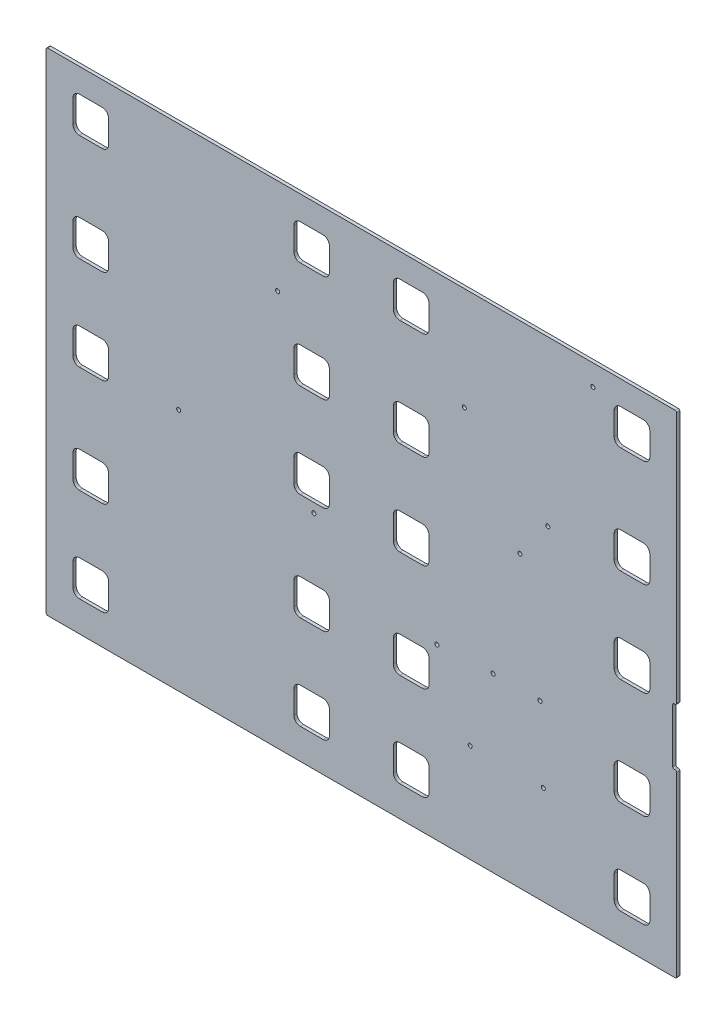
SolidWorks part; units mm, degrees
material "PP Film"
ref_plane "X-Y Datum" through (0, 0, 0) normal (0, 0, 1) x (1, 0, 0)
ref_plane "X-Z Datum" through (0, 0, 0) normal (0, 1, 0) x (1, 0, 0)
ref_plane "Y-Z Datum" through (0, 0, 0) normal (1, 0, 0) x (0, 0, -1)
sketch "Sketch9" plane through (0, 0, 0) normal (0, 0, 1) x (1, 0, 0)
  line L0 (-82.7559, -182.5893) -> (-82.7583, -160.1613) construction
  line L1 (-89.109, -153.8119) -> (-111.537, -153.8143) construction
  line L2 (-117.8863, -160.165) -> (-117.8839, -182.593) construction
  line L3 (-111.5333, -188.9423) -> (-89.1053, -188.9399) construction
  line L4 (476.8831, 172.8027) -> (-144.3755, 172.7375)
  line L12 (-111.5443, -83.8117) -> (-89.1163, -83.8093) construction
  line L13 (-82.767, -77.4587) -> (-82.7693, -55.0307) construction
  line L14 (-89.12, -48.6813) -> (-111.548, -48.6837) construction
  line L15 (-117.8973, -55.0344) -> (-117.895, -77.4624) construction
  line L16 (-82.7877, 120.2549) -> (-82.7901, 142.6829) construction
  line L17 (-89.1408, 149.0323) -> (-111.5688, 149.0299) construction
  line L18 (-117.9181, 142.6792) -> (-117.9157, 120.2512) construction
  line L19 (-111.5651, 113.9019) -> (-89.1371, 113.9043) construction
  line L20 (-111.554, 8.7713) -> (-89.126, 8.7737) construction
  line L21 (-117.9071, 37.5486) -> (-117.9047, 15.1206) construction
  line L22 (-89.1297, 43.9017) -> (-111.5577, 43.8993) construction
  line L23 (-82.7767, 15.1243) -> (-82.7791, 37.5523) construction
  line L24 (-82.7559, -182.5893) -> (-82.7583, -160.1613)
  line L25 (-89.109, -153.8119) -> (-111.537, -153.8143)
  line L26 (-117.8863, -160.165) -> (-117.8839, -182.593)
  line L27 (-111.5333, -188.9423) -> (-89.1053, -188.9399)
  line L28 (-111.5443, -83.8117) -> (-89.1163, -83.8093)
  line L29 (-82.767, -77.4587) -> (-82.7693, -55.0307)
  line L30 (-89.12, -48.6813) -> (-111.548, -48.6837)
  line L31 (-117.8973, -55.0344) -> (-117.895, -77.4624)
  line L32 (-82.7877, 120.2549) -> (-82.7901, 142.6829)
  line L33 (-89.1408, 149.0323) -> (-111.5688, 149.0299)
  line L34 (-117.9181, 142.6792) -> (-117.9157, 120.2512)
  line L35 (-111.5651, 113.9019) -> (-89.1371, 113.9043)
  line L36 (-111.554, 8.7713) -> (-89.126, 8.7737)
  line L37 (-117.9071, 37.5486) -> (-117.9047, 15.1206)
  line L38 (-89.1297, 43.9017) -> (-111.5577, 43.8993)
  line L39 (-82.7767, 15.1243) -> (-82.7791, 37.5523)
  line L40 (-82.7462, -275.1723) -> (-82.7486, -252.7443) construction
  line L41 (-89.0992, -246.3949) -> (-111.5272, -246.3973) construction
  line L42 (-117.8766, -252.748) -> (-117.8742, -275.176) construction
  line L43 (-111.5235, -281.5253) -> (-89.0955, -281.5229) construction
  line L44 (-82.7462, -275.1723) -> (-82.7486, -252.7443)
  line L45 (-89.0992, -246.3949) -> (-111.5272, -246.3973)
  line L46 (-117.8766, -252.748) -> (-117.8742, -275.176)
  line L47 (-111.5235, -281.5253) -> (-89.0955, -281.5229)
  line L82 (476.8831, 172.8027) -> (-144.3755, 172.7375)
  line L83 (-144.3755, 172.7375) -> (-144.3246, -311.5135)
  line L84 (-144.3755, 172.7375) -> (-144.3246, -311.5135)
  line L85 (-144.3246, -311.5135) -> (476.934, -311.4483)
  line L86 (-144.3246, -311.5135) -> (476.934, -311.4483)
  line L87 (476.934, -311.4483) -> (476.8831, 172.8027)
  line L88 (476.934, -311.4483) -> (476.8831, 172.8027)
  arc A0 (-89.1053, -188.9399) -> (-82.7559, -182.5893) centre (-89.1059, -182.5899) ccw construction
  arc A1 (-82.7583, -160.1613) -> (-89.109, -153.8119) centre (-89.1083, -160.1619) ccw construction
  arc A2 (-111.537, -153.8143) -> (-117.8863, -160.165) centre (-111.5363, -160.1643) ccw construction
  arc A3 (-117.8839, -182.593) -> (-111.5333, -188.9423) centre (-111.5339, -182.5923) ccw construction
  arc A4 (-89.1163, -83.8093) -> (-82.767, -77.4587) centre (-89.117, -77.4593) ccw construction
  arc A5 (-82.7693, -55.0307) -> (-89.12, -48.6813) centre (-89.1193, -55.0313) ccw construction
  arc A6 (-111.548, -48.6837) -> (-117.8973, -55.0344) centre (-111.5473, -55.0337) ccw construction
  arc A7 (-117.895, -77.4624) -> (-111.5443, -83.8117) centre (-111.545, -77.4617) ccw construction
  arc A8 (-89.1371, 113.9043) -> (-82.7877, 120.2549) centre (-89.1377, 120.2543) ccw construction
  arc A9 (-82.7901, 142.6829) -> (-89.1408, 149.0323) centre (-89.1401, 142.6823) ccw construction
  arc A10 (-111.5688, 149.0299) -> (-117.9181, 142.6792) centre (-111.5681, 142.6799) ccw construction
  arc A11 (-117.9157, 120.2512) -> (-111.5651, 113.9019) centre (-111.5657, 120.2519) ccw construction
  arc A12 (-82.7791, 37.5523) -> (-89.1297, 43.9017) centre (-89.1291, 37.5517) ccw construction
  arc A13 (-89.126, 8.7737) -> (-82.7767, 15.1243) centre (-89.1267, 15.1237) ccw construction
  arc A14 (-117.9047, 15.1206) -> (-111.554, 8.7713) centre (-111.5547, 15.1213) ccw construction
  arc A15 (-111.5577, 43.8993) -> (-117.9071, 37.5486) centre (-111.5571, 37.5493) ccw construction
  arc A16 (-89.1053, -188.9399) -> (-82.7559, -182.5893) centre (-89.1059, -182.5899) ccw
  arc A17 (-82.7583, -160.1613) -> (-89.109, -153.8119) centre (-89.1083, -160.1619) ccw
  arc A18 (-111.537, -153.8143) -> (-117.8863, -160.165) centre (-111.5363, -160.1643) ccw
  arc A19 (-117.8839, -182.593) -> (-111.5333, -188.9423) centre (-111.5339, -182.5923) ccw
  arc A20 (-89.1163, -83.8093) -> (-82.767, -77.4587) centre (-89.117, -77.4593) ccw
  arc A21 (-82.7693, -55.0307) -> (-89.12, -48.6813) centre (-89.1193, -55.0313) ccw
  arc A22 (-111.548, -48.6837) -> (-117.8973, -55.0344) centre (-111.5473, -55.0337) ccw
  arc A23 (-117.895, -77.4624) -> (-111.5443, -83.8117) centre (-111.545, -77.4617) ccw
  arc A24 (-89.1371, 113.9043) -> (-82.7877, 120.2549) centre (-89.1377, 120.2543) ccw
  arc A25 (-82.7901, 142.6829) -> (-89.1408, 149.0323) centre (-89.1401, 142.6823) ccw
  arc A26 (-111.5688, 149.0299) -> (-117.9181, 142.6792) centre (-111.5681, 142.6799) ccw
  arc A27 (-117.9157, 120.2512) -> (-111.5651, 113.9019) centre (-111.5657, 120.2519) ccw
  arc A28 (-82.7791, 37.5523) -> (-89.1297, 43.9017) centre (-89.1291, 37.5517) ccw
  arc A29 (-89.126, 8.7737) -> (-82.7767, 15.1243) centre (-89.1267, 15.1237) ccw
  arc A30 (-117.9047, 15.1206) -> (-111.554, 8.7713) centre (-111.5547, 15.1213) ccw
  arc A31 (-111.5577, 43.8993) -> (-117.9071, 37.5486) centre (-111.5571, 37.5493) ccw
  arc A32 (-89.0955, -281.5229) -> (-82.7462, -275.1723) centre (-89.0962, -275.1729) ccw construction
  arc A33 (-111.5272, -246.3973) -> (-117.8766, -252.748) centre (-111.5266, -252.7473) ccw construction
  arc A34 (-117.8742, -275.176) -> (-111.5235, -281.5253) centre (-111.5242, -275.1753) ccw construction
  arc A35 (-89.0955, -281.5229) -> (-82.7462, -275.1723) centre (-89.0962, -275.1729) ccw
  arc A36 (-111.5272, -246.3973) -> (-117.8766, -252.748) centre (-111.5266, -252.7473) ccw
  arc A37 (-117.8742, -275.176) -> (-111.5235, -281.5253) centre (-111.5242, -275.1753) ccw
  arc A38 (-82.7486, -252.7443) -> (-89.0992, -246.3949) centre (-89.0986, -252.7449) ccw construction
  arc A39 (-82.7486, -252.7443) -> (-89.0992, -246.3949) centre (-89.0986, -252.7449) ccw
  dimension "D1" = 0
extrude "Boss-Extrude2" add sketch "Sketch9" along normal blind 3.175
sketch "Sketch10" plane through (0, 0, 3.175) normal (0, 0, 1) x (1, 0, 0)
  line L9 (476.8831, 172.8027) -> (-144.3755, 172.7375)
  line L10 (-144.3755, 172.7375) -> (-144.3246, -311.5135)
  line L11 (-144.3246, -311.5135) -> (476.934, -311.4483)
  line L12 (-117.8863, -160.165) -> (-117.8839, -182.593)
  line L13 (-111.5333, -188.9423) -> (-89.1053, -188.9399)
  line L14 (-82.7559, -182.5893) -> (-82.7583, -160.1613)
  line L15 (-89.109, -153.8119) -> (-111.537, -153.8143)
  line L16 (-117.8863, -160.165) -> (-117.8839, -182.593)
  line L17 (-111.5333, -188.9423) -> (-89.1053, -188.9399)
  line L18 (-82.7559, -182.5893) -> (-82.7583, -160.1613)
  line L19 (-89.109, -153.8119) -> (-111.537, -153.8143)
  line L20 (-117.8766, -252.748) -> (-117.8742, -275.176)
  line L21 (-89.0992, -246.3949) -> (-111.5272, -246.3973)
  line L22 (-82.7462, -275.1723) -> (-82.7486, -252.7443)
  line L23 (-111.5235, -281.5253) -> (-89.0955, -281.5229)
  line L24 (-117.8766, -252.748) -> (-117.8742, -275.176)
  line L25 (-89.0992, -246.3949) -> (-111.5272, -246.3973)
  line L26 (-82.7462, -275.1723) -> (-82.7486, -252.7443)
  line L27 (-111.5235, -281.5253) -> (-89.0955, -281.5229)
  line L28 (-89.12, -48.6813) -> (-111.548, -48.6837)
  line L29 (-117.8973, -55.0344) -> (-117.895, -77.4624)
  line L30 (-111.5443, -83.8117) -> (-89.1163, -83.8093)
  line L31 (-82.767, -77.4587) -> (-82.7693, -55.0307)
  line L32 (-89.12, -48.6813) -> (-111.548, -48.6837)
  line L33 (-117.8973, -55.0344) -> (-117.895, -77.4624)
  line L34 (-111.5443, -83.8117) -> (-89.1163, -83.8093)
  line L35 (-82.767, -77.4587) -> (-82.7693, -55.0307)
  line L36 (-82.7877, 120.2549) -> (-82.7901, 142.6829)
  line L37 (-111.5651, 113.9019) -> (-89.1371, 113.9043)
  line L38 (-117.9181, 142.6792) -> (-117.9157, 120.2512)
  line L39 (-89.1408, 149.0323) -> (-111.5688, 149.0299)
  line L40 (-82.7877, 120.2549) -> (-82.7901, 142.6829)
  line L41 (-111.5651, 113.9019) -> (-89.1371, 113.9043)
  line L42 (-117.9181, 142.6792) -> (-117.9157, 120.2512)
  line L43 (-89.1408, 149.0323) -> (-111.5688, 149.0299)
  line L44 (-111.554, 8.7713) -> (-89.126, 8.7737)
  line L45 (-82.7767, 15.1243) -> (-82.7791, 37.5523)
  line L46 (-89.1297, 43.9017) -> (-111.5577, 43.8993)
  line L47 (-117.9071, 37.5486) -> (-117.9047, 15.1206)
  line L48 (-111.554, 8.7713) -> (-89.126, 8.7737)
  line L49 (-82.7767, 15.1243) -> (-82.7791, 37.5523)
  line L50 (-89.1297, 43.9017) -> (-111.5577, 43.8993)
  line L51 (-117.9071, 37.5486) -> (-117.9047, 15.1206)
  line L53 (476.934, -311.4483) -> (476.8831, 172.8027)
  arc A4 (-117.8839, -182.593) -> (-111.5333, -188.9423) centre (-111.5339, -182.5923) ccw
  arc A5 (-89.1053, -188.9399) -> (-82.7559, -182.5893) centre (-89.1059, -182.5899) ccw
  arc A6 (-82.7583, -160.1613) -> (-89.109, -153.8119) centre (-89.1083, -160.1619) ccw
  arc A7 (-111.537, -153.8143) -> (-117.8863, -160.165) centre (-111.5363, -160.1643) ccw
  arc A8 (-117.8839, -182.593) -> (-111.5333, -188.9423) centre (-111.5339, -182.5923) ccw
  arc A9 (-89.1053, -188.9399) -> (-82.7559, -182.5893) centre (-89.1059, -182.5899) ccw
  arc A10 (-82.7583, -160.1613) -> (-89.109, -153.8119) centre (-89.1083, -160.1619) ccw
  arc A11 (-111.537, -153.8143) -> (-117.8863, -160.165) centre (-111.5363, -160.1643) ccw
  arc A12 (-111.5272, -246.3973) -> (-117.8766, -252.748) centre (-111.5266, -252.7473) ccw
  arc A13 (-82.7486, -252.7443) -> (-89.0992, -246.3949) centre (-89.0986, -252.7449) ccw
  arc A14 (-89.0955, -281.5229) -> (-82.7462, -275.1723) centre (-89.0962, -275.1729) ccw
  arc A15 (-117.8742, -275.176) -> (-111.5235, -281.5253) centre (-111.5242, -275.1753) ccw
  arc A16 (-111.5272, -246.3973) -> (-117.8766, -252.748) centre (-111.5266, -252.7473) ccw
  arc A17 (-82.7486, -252.7443) -> (-89.0992, -246.3949) centre (-89.0986, -252.7449) ccw
  arc A18 (-89.0955, -281.5229) -> (-82.7462, -275.1723) centre (-89.0962, -275.1729) ccw
  arc A19 (-117.8742, -275.176) -> (-111.5235, -281.5253) centre (-111.5242, -275.1753) ccw
  arc A20 (-111.548, -48.6837) -> (-117.8973, -55.0344) centre (-111.5473, -55.0337) ccw
  arc A21 (-117.895, -77.4624) -> (-111.5443, -83.8117) centre (-111.545, -77.4617) ccw
  arc A22 (-89.1163, -83.8093) -> (-82.767, -77.4587) centre (-89.117, -77.4593) ccw
  arc A23 (-82.7693, -55.0307) -> (-89.12, -48.6813) centre (-89.1193, -55.0313) ccw
  arc A24 (-111.548, -48.6837) -> (-117.8973, -55.0344) centre (-111.5473, -55.0337) ccw
  arc A25 (-117.895, -77.4624) -> (-111.5443, -83.8117) centre (-111.545, -77.4617) ccw
  arc A26 (-89.1163, -83.8093) -> (-82.767, -77.4587) centre (-89.117, -77.4593) ccw
  arc A27 (-82.7693, -55.0307) -> (-89.12, -48.6813) centre (-89.1193, -55.0313) ccw
  arc A28 (-89.1371, 113.9043) -> (-82.7877, 120.2549) centre (-89.1377, 120.2543) ccw
  arc A29 (-117.9157, 120.2512) -> (-111.5651, 113.9019) centre (-111.5657, 120.2519) ccw
  arc A30 (-111.5688, 149.0299) -> (-117.9181, 142.6792) centre (-111.5681, 142.6799) ccw
  arc A31 (-82.7901, 142.6829) -> (-89.1408, 149.0323) centre (-89.1401, 142.6823) ccw
  arc A32 (-89.1371, 113.9043) -> (-82.7877, 120.2549) centre (-89.1377, 120.2543) ccw
  arc A33 (-117.9157, 120.2512) -> (-111.5651, 113.9019) centre (-111.5657, 120.2519) ccw
  arc A34 (-111.5688, 149.0299) -> (-117.9181, 142.6792) centre (-111.5681, 142.6799) ccw
  arc A35 (-82.7901, 142.6829) -> (-89.1408, 149.0323) centre (-89.1401, 142.6823) ccw
  arc A36 (-89.126, 8.7737) -> (-82.7767, 15.1243) centre (-89.1267, 15.1237) ccw
  arc A37 (-82.7791, 37.5523) -> (-89.1297, 43.9017) centre (-89.1291, 37.5517) ccw
  arc A38 (-111.5577, 43.8993) -> (-117.9071, 37.5486) centre (-111.5571, 37.5493) ccw
  arc A39 (-117.9047, 15.1206) -> (-111.554, 8.7713) centre (-111.5547, 15.1213) ccw
  arc A40 (-89.126, 8.7737) -> (-82.7767, 15.1243) centre (-89.1267, 15.1237) ccw
  arc A41 (-82.7791, 37.5523) -> (-89.1297, 43.9017) centre (-89.1291, 37.5517) ccw
  arc A42 (-111.5577, 43.8993) -> (-117.9071, 37.5486) centre (-111.5571, 37.5493) ccw
  arc A43 (-117.9047, 15.1206) -> (-111.554, 8.7713) centre (-111.5547, 15.1213) ccw
  dimension "D2" = 0
  dimension "D3" = 0
  dimension "D4" = 0
  dimension "D5" = 0
  dimension "D6" = 0
extrude "Cut-Extrude6" cut sketch "Sketch10" against normal through all contours L40 A35 L43 A34 L42 A33 L41 A32 | L51 A43 L48 A40 L49 A41 L50 A42 | L35 A27 L32 A24 L33 A25 L34 A26 | L19 A11 L16 A8 L17 A9 L18 A10 | L24 A19 L27 A18 L26 A17 L25 A16
pattern_linear "LPattern2" count 2 spacing 217.5764 along (1, 0.0001, 0) of "Cut-Extrude6"
ref_plane "Plane1" through (166.272, 0.0175, 0) normal (-1, -0.0001, 0) x (0, 0, 1)
mirror "Mirror1" about plane through (166.272, 0.0175, 0) normal (-1, -0.0001, 0) of "LPattern2", "Cut-Extrude6"
sketch "Sketch11" plane through (0, 0, 3.175) normal (0, 0, 1) x (1, 0, 0)
  circle A3 centre (296.0387, -141.6048) radius 1.9939
  circle A5 centre (296.0387, -141.6048) radius 1.9939
  circle A7 centre (394.3353, 152.1565) radius 1.9939
  circle A9 centre (394.3353, 152.1565) radius 1.9939
  circle A11 centre (267.6913, 71.3582) radius 1.9939
  circle A13 centre (267.6913, 71.3582) radius 1.9939
  circle A15 centre (83.7969, 78.6239) radius 1.9939
  circle A17 centre (83.7969, 78.6239) radius 1.9939
  circle A19 centre (-13.7373, -71.3863) radius 1.9939
  circle A21 centre (-13.7373, -71.3863) radius 1.9939
  circle A23 centre (349.9236, 11.0749) radius 1.9939
  circle A44 centre (349.9236, 11.0749) radius 1.9939
  circle A45 centre (322.4275, -26.052) radius 1.9939
  circle A46 centre (322.4275, -26.052) radius 1.9939
  circle A47 centre (342.2387, -141.5999) radius 1.9939
  circle A48 centre (342.2387, -141.5999) radius 1.9939
  circle A49 centre (345.5113, -214.3496) radius 1.9939
  circle A50 centre (345.5113, -214.3496) radius 1.9939
  circle A51 centre (119.4061, -93.0712) radius 1.9939
  circle A52 centre (119.4061, -93.0712) radius 1.9939
  circle A53 centre (240.6965, -144.4935) radius 1.9939
  circle A54 centre (240.6965, -144.4935) radius 1.9939
  circle A55 centre (273.5113, -214.3572) radius 1.9939
  circle A56 centre (273.5113, -214.3572) radius 1.9939
  dimension "D1" = 0
  dimension "D2" = 0
  dimension "D3" = 0
  dimension "D4" = 0
  dimension "D5" = 0
  dimension "D6" = 0
  dimension "D7" = 0
  dimension "D8" = 0
  dimension "D9" = 0
  dimension "D10" = 0
  dimension "D11" = 0
  dimension "D12" = 0
extrude "Cut-Extrude7" cut sketch "Sketch11" against normal through all
sketch "Sketch12" plane through (0, 0, 3.175) normal (0, 0, 1) x (1, 0, 0)
  line L0 (472.9633, -129.0942) -> (472.9585, -83.0942)
  line L1 (472.9632, -127.919) -> (472.9635, -130.2694) construction
  line L2 (472.9584, -81.919) -> (472.9586, -84.2694) construction
  line L3 (476.934, -311.4483) -> (476.8831, 172.8027) construction
  line L4 (472.9609, -78.1542) -> (472.9609, -134.0342)
  line L5 (472.9609, -134.0342) -> (476.9154, -134.0342)
  line L6 (472.9609, -78.1542) -> (476.9095, -78.1542)
  line L9 (476.934, -311.4483) -> (476.8831, 172.8027)
  point P11 (472.9609, -106.0942)
  dimension "D1" = 46
  dimension "D2" = 55.88
extrude "Cut-Extrude8" cut sketch "Sketch12" against normal through all
fillet "Fillet1" radius 1.5875 8 edges at (472.9609, -78.1542, 1.5875) (472.9609, -134.0342, 1.5875) (476.9095, -78.1542, 1.5875) (476.9154, -134.0342, 1.5875) (476.934, -311.4483, 1.5875) (-144.3246, -311.5135, 1.5875) (-144.3755, 172.7375, 1.5875) (476.8831, 172.8027, 1.5875)
